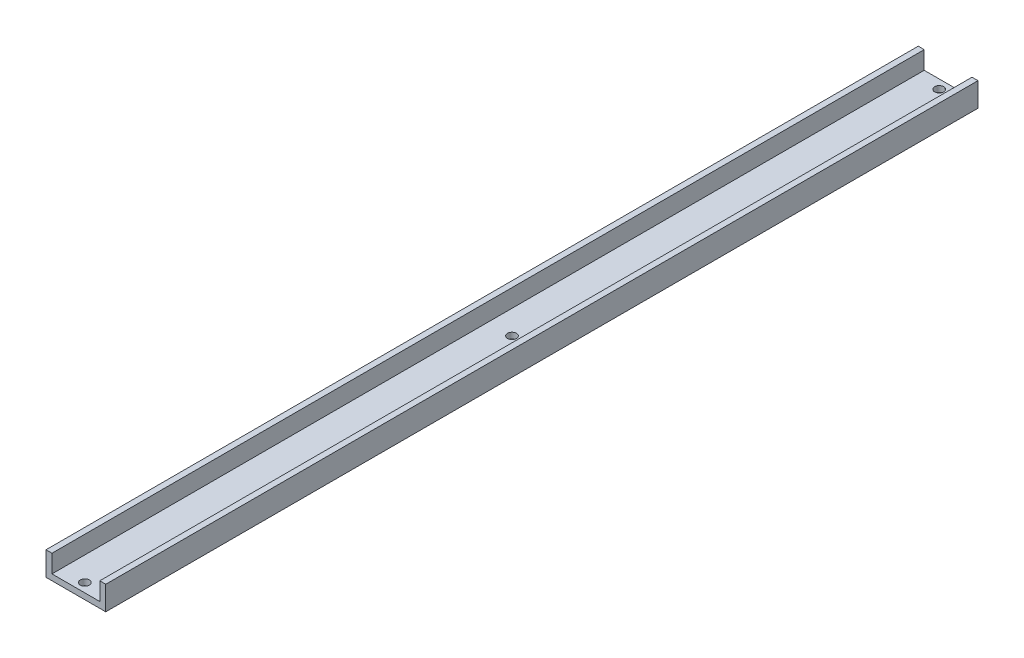
SolidWorks part; units mm, degrees
ref_plane "Front Plane" through (0, 0, 0) normal (0, 0, 1) x (1, 0, 0)
ref_plane "Top Plane" through (0, 0, 0) normal (0, 1, 0) x (1, 0, 0)
ref_plane "Right Plane" through (0, 0, 0) normal (1, 0, 0) x (0, 0, -1)
sketch "Sketch1" plane through (0, 0, 0) normal (0, 0, 1) x (1, 0, 0)
  line L0 (3.175, 3.175) -> (3.175, 12.7)
  line L1 (0, 0) -> (31.75, 0)
  line L2 (0, 0) -> (0, 12.7)
  line L4 (31.75, 0) -> (31.75, 12.7)
  line L5 (3.175, 3.175) -> (28.575, 3.175)
  line L6 (28.575, 3.175) -> (28.575, 12.7)
  line L7 (0, 12.7) -> (3.175, 12.7)
  line L8 (31.75, 12.7) -> (28.575, 12.7)
  dimension "D1" = 31.75
  dimension "D2" = 12.7
  dimension "D3" = 3.175
extrude "Boss-Extrude1" add sketch "Sketch1" along normal blind 463.55
sketch "Sketch2" plane through (0, 3.175, 0) normal (0, 1, 0) x (1, 0, 0)
  line L0 (15.875, -463.55) -> (15.875, -458.7875) construction
  line L1 (28.575, -463.55) -> (3.175, -463.55) construction
  line L2 (15.875, 0) -> (15.875, -4.7625) construction
  line L3 (28.575, 0) -> (3.175, 0) construction
  circle A0 centre (15.875, -458.7875) radius 2.413
  circle A1 centre (15.875, -4.7625) radius 2.413
  dimension "D2" = 4.826
  dimension "D4" = 4.826
  dimension "D1" = 4.7625
  dimension "D3" = 4.7625
extrude "Cut-Extrude1" cut sketch "Sketch2" against normal up to next
sketch "Sketch3" plane through (0, 3.175, 0) normal (0, 1, 0) x (1, 0, 0)
  line L0 (28.575, -231.775) -> (15.875, -231.775) construction
  line L1 (28.575, -463.55) -> (28.575, 0) construction
  circle A0 centre (15.875, -231.775) radius 2.413
  dimension "D2" = 4.826
  dimension "D1" = 12.7
extrude "Cut-Extrude2" cut sketch "Sketch3" against normal up to next
